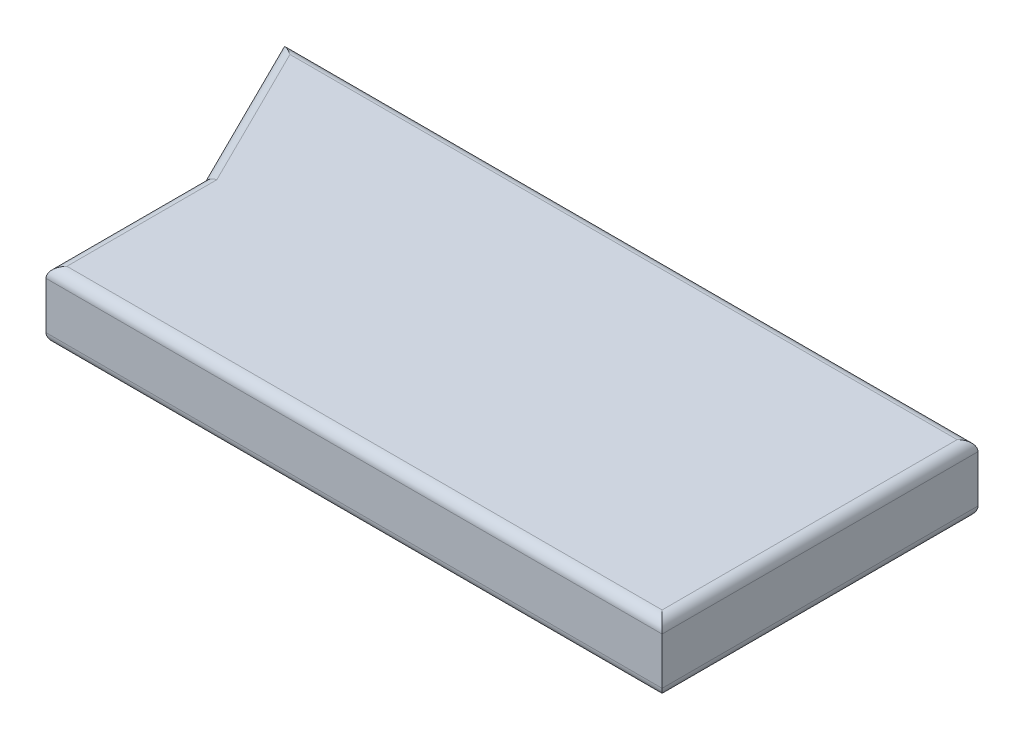
SolidWorks part; units mm, degrees
ref_plane "前视基准面" through (0, 0, 0) normal (0, 0, 1) x (1, 0, 0)
ref_plane "上视基准面" through (0, 0, 0) normal (0, 1, 0) x (1, 0, 0)
ref_plane "右视基准面" through (0, 0, 0) normal (1, 0, 0) x (0, 0, -1)
other "Configuration Table"
sketch "草图1" plane through (0, 0, 0) normal (0, 1, 0) x (1, 0, 0)
  line L0 (-59, 30.25) -> (-74, 30.25)
  line L1 (-59, -30.25) -> (59, -30.25)
  line L2 (-59, -30.25) -> (-59, 30.25)
  line L3 (-59, 30.25) -> (59, 30.25)
  line L4 (59, -30.25) -> (59, 30.25)
  line L5 (-59, -30.25) -> (59, 30.25) construction
  line L6 (-59, 30.25) -> (59, -30.25) construction
  line L7 (-74, 30.25) -> (-59, 0)
  point P0 (0, 0)
  point P6 (-59, 0)
  dimension "D1" = 60.5
  dimension "D2" = 118
  dimension "D3" = 15
extrude "凸台-拉伸1" add sketch "草图1" along normal blind 13 contours L0 L7 L2 | L1 L4 L3 L2
fillet "圆角1" radius 2 5 edges at (59, 13, 0) (0, 13, 30.25) (-59, 13, 15.125) (-66.5, 13, -15.125) (-7.5, 13, -30.25)
fillet "圆角2" radius 2 5 edges at (-66.5, 0, -15.125) (-59, 0, 15.125) (0, 0, 30.25) (59, 0, 0) (-7.5, 0, -30.25)
